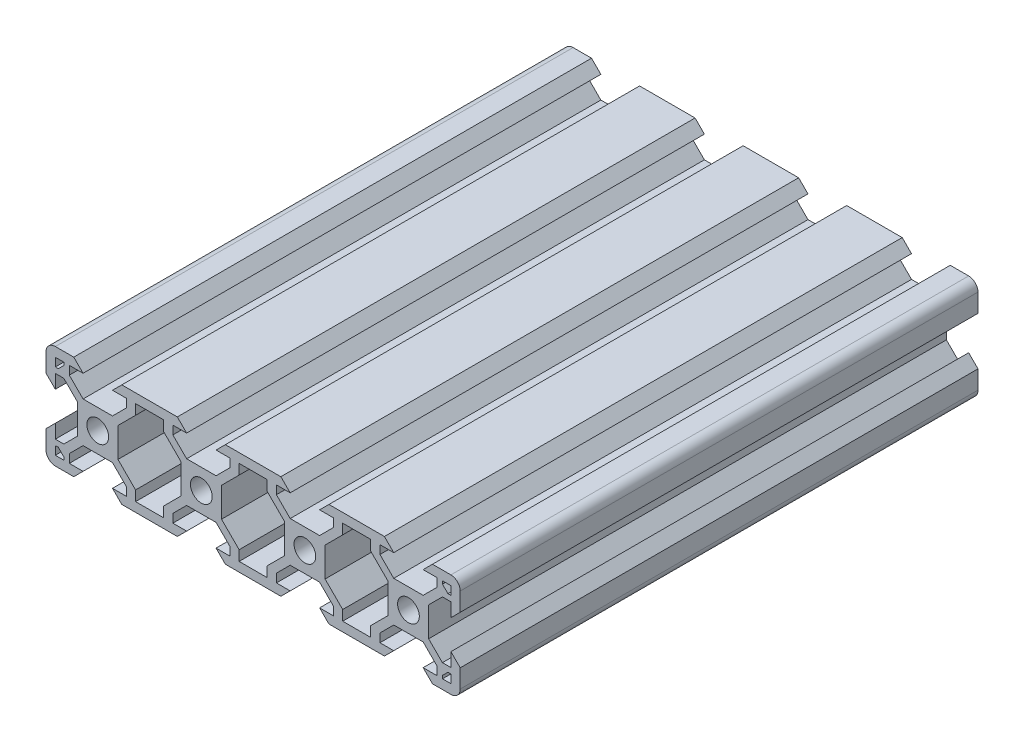
SolidWorks part; units mm, degrees
material "5052-H38, Barre (SS)"
ref_plane "Plan de face" through (0, 0, 0) normal (0, 0, 1) x (1, 0, 0)
ref_plane "Plan de dessus" through (0, 0, 0) normal (0, 1, 0) x (1, 0, 0)
ref_plane "Plan de droite" through (0, 0, 0) normal (1, 0, 0) x (0, 0, -1)
sketch "Esquisse1" plane through (0, 0, 0) normal (0, 0, 1) x (1, 0, 0)
  line L0 (0, 0) -> (0, 10) construction
  line L1 (0, 0) -> (-40, 0) construction
  line L2 (-40, 10) -> (-30, 0) construction
  line L3 (-30, 0) -> (-20, 10) construction
  line L4 (-20, 10) -> (-10, 0) construction
  line L5 (-10, 0) -> (0, 10) construction
  line L6 (-10, 0) -> (-10, 10) construction
  line L7 (-20, 10) -> (-20, 0) construction
  line L8 (-40, 0) -> (-40, 10) construction
  line L9 (-38.2, 10) -> (-34.64, 10)
  line L10 (-34.64, 10) -> (-32.84, 8.2)
  line L11 (-32.84, 8.2) -> (-35.4993, 8.2)
  line L12 (-35.4993, 8.2) -> (-35.4993, 6.56)
  line L13 (-35.4993, 6.56) -> (-32.84, 3.9007)
  line L14 (-32.84, 3.9007) -> (-27.16, 3.9007)
  line L15 (-30, 0) -> (-30, 10) construction
  line L16 (-33.9007, 2.84) -> (-33.9007, 0)
  line L17 (-36.56, 5.4993) -> (-33.9007, 2.84)
  line L18 (-38.2, 5.4993) -> (-36.56, 5.4993)
  line L19 (-38.2, 2.84) -> (-38.2, 5.4993)
  line L20 (-40, 4.64) -> (-38.2, 2.84)
  line L21 (-40, 8.2) -> (-40, 4.64)
  line L22 (-38.2, 8.2) -> (-38.2, 6.5693)
  line L23 (-38.2, 6.5693) -> (-37.63, 6.5693)
  line L24 (-37.63, 6.5693) -> (-36.5693, 7.63)
  line L25 (-36.5693, 7.63) -> (-36.5693, 8.2)
  line L26 (-36.5693, 8.2) -> (-38.2, 8.2)
  line L27 (-17.3, 6.2393) -> (-17.3, 8.2)
  line L28 (-13.9007, 2.84) -> (-17.3, 6.2393)
  line L29 (-13.9007, -2.84) -> (-13.9007, 2.84)
  line L30 (-14.64, 10) -> (-12.84, 8.2)
  line L31 (-12.84, 8.2) -> (-15.4993, 8.2)
  line L32 (-15.4993, 8.2) -> (-15.4993, 6.56)
  line L33 (-15.4993, 6.56) -> (-12.84, 3.9007)
  line L34 (-12.84, 3.9007) -> (-7.16, 3.9007)
  line L35 (-5.36, 10) -> (-7.16, 8.2)
  line L36 (-7.16, 8.2) -> (-4.5007, 8.2)
  line L37 (-4.5007, 8.2) -> (-4.5007, 6.56)
  line L38 (-4.5007, 6.56) -> (-7.16, 3.9007)
  line L39 (-5.36, 10) -> (5.36, 10)
  line L40 (-6.0993, -2.84) -> (-6.0993, 2.84)
  line L41 (-6.0993, 2.84) -> (-2.7, 6.2393)
  line L42 (-2.7, 6.2393) -> (-2.7, 8.2)
  line L43 (-2.7, 8.2) -> (2.7, 8.2)
  line L44 (-25.36, 10) -> (-27.16, 8.2)
  line L45 (-7.16, 3.9007) -> (-6.0993, 2.84) construction
  line L46 (-36.5693, -7.63) -> (-36.5693, -8.2)
  line L47 (-37.63, -6.5693) -> (-36.5693, -7.63)
  line L48 (-38.2, -6.5693) -> (-37.63, -6.5693)
  line L49 (-38.2, -8.2) -> (-38.2, -6.5693)
  line L50 (-27.16, 8.2) -> (-24.5007, 8.2)
  line L51 (-24.5007, 8.2) -> (-24.5007, 6.56)
  line L52 (-24.5007, 6.56) -> (-27.16, 3.9007)
  line L53 (-25.36, 10) -> (-14.64, 10)
  line L54 (-26.0993, -2.84) -> (-26.0993, 2.84)
  line L55 (-26.0993, 2.84) -> (-22.7, 6.2393)
  line L56 (-22.7, 6.2393) -> (-22.7, 8.2)
  line L57 (-22.7, 8.2) -> (-17.3, 8.2)
  line L58 (-27.16, 3.9007) -> (-26.0993, 2.84) construction
  line L59 (-26.0993, 2.84) -> (-26.0962, 2.8177) construction
  line L60 (-36.5693, -8.2) -> (-38.2, -8.2)
  line L61 (-26.0993, -2.84) -> (-22.7, -6.2393)
  line L62 (-22.7, -6.2393) -> (-22.7, -8.2)
  line L63 (-22.7, -8.2) -> (-17.3, -8.2)
  line L64 (-17.3, -6.2393) -> (-17.3, -8.2)
  line L65 (-13.9007, -2.84) -> (-17.3, -6.2393)
  line L66 (-2.7, -8.2) -> (2.7, -8.2)
  line L67 (-2.7, -6.2393) -> (-2.7, -8.2)
  line L68 (-6.0993, -2.84) -> (-2.7, -6.2393)
  line L69 (-5.36, -10) -> (5.36, -10)
  line L70 (-5.36, -10) -> (-7.16, -8.2)
  line L71 (-7.16, -8.2) -> (-4.5007, -8.2)
  line L72 (-4.5007, -8.2) -> (-4.5007, -6.56)
  line L73 (-4.5007, -6.56) -> (-7.16, -3.9007)
  line L74 (-12.84, -3.9007) -> (-7.16, -3.9007)
  line L75 (-15.4993, -6.56) -> (-12.84, -3.9007)
  line L76 (-15.4993, -8.2) -> (-15.4993, -6.56)
  line L77 (-12.84, -8.2) -> (-15.4993, -8.2)
  line L78 (-14.64, -10) -> (-12.84, -8.2)
  line L79 (-25.36, -10) -> (-14.64, -10)
  line L80 (-25.36, -10) -> (-27.16, -8.2)
  line L81 (-27.16, -8.2) -> (-24.5007, -8.2)
  line L82 (-24.5007, -8.2) -> (-24.5007, -6.56)
  line L83 (-24.5007, -6.56) -> (-27.16, -3.9007)
  line L84 (-32.84, -3.9007) -> (-27.16, -3.9007)
  line L85 (-35.4993, -6.56) -> (-32.84, -3.9007)
  line L86 (-35.4993, -8.2) -> (-35.4993, -6.56)
  line L87 (-32.84, -8.2) -> (-35.4993, -8.2)
  line L88 (-34.64, -10) -> (-32.84, -8.2)
  line L89 (-38.2, -10) -> (-34.64, -10)
  line L90 (-40, -8.2) -> (-40, -4.64)
  line L91 (-40, -4.64) -> (-38.2, -2.84)
  line L92 (-38.2, -2.84) -> (-38.2, -5.4993)
  line L93 (-38.2, -5.4993) -> (-36.56, -5.4993)
  line L94 (-36.56, -5.4993) -> (-33.9007, -2.84)
  line L95 (-33.9007, -2.84) -> (-33.9007, 0)
  line L96 (36.5693, 8.2) -> (38.2, 8.2)
  line L97 (36.5693, 7.63) -> (36.5693, 8.2)
  line L98 (37.63, 6.5693) -> (36.5693, 7.63)
  line L99 (38.2, 6.5693) -> (37.63, 6.5693)
  line L100 (38.2, 8.2) -> (38.2, 6.5693)
  line L101 (36.5693, -8.2) -> (38.2, -8.2)
  line L102 (36.5693, -7.63) -> (36.5693, -8.2)
  line L103 (37.63, -6.5693) -> (36.5693, -7.63)
  line L104 (38.2, -6.5693) -> (37.63, -6.5693)
  line L105 (38.2, -8.2) -> (38.2, -6.5693)
  line L106 (13.9007, -2.84) -> (17.3, -6.2393)
  line L107 (17.3, -6.2393) -> (17.3, -8.2)
  line L108 (22.7, -8.2) -> (17.3, -8.2)
  line L109 (22.7, -6.2393) -> (22.7, -8.2)
  line L110 (26.0993, -2.84) -> (22.7, -6.2393)
  line L111 (26.0993, -2.84) -> (26.0993, 2.84)
  line L112 (26.0993, 2.84) -> (22.7, 6.2393)
  line L113 (22.7, 6.2393) -> (22.7, 8.2)
  line L114 (22.7, 8.2) -> (17.3, 8.2)
  line L115 (17.3, 6.2393) -> (17.3, 8.2)
  line L116 (13.9007, 2.84) -> (17.3, 6.2393)
  line L117 (13.9007, -2.84) -> (13.9007, 2.84)
  line L118 (2.7, -6.2393) -> (2.7, -8.2)
  line L119 (6.0993, -2.84) -> (2.7, -6.2393)
  line L120 (6.0993, -2.84) -> (6.0993, 2.84)
  line L121 (6.0993, 2.84) -> (2.7, 6.2393)
  line L122 (2.7, 6.2393) -> (2.7, 8.2)
  line L123 (5.36, -10) -> (7.16, -8.2)
  line L124 (7.16, -8.2) -> (4.5007, -8.2)
  line L125 (4.5007, -8.2) -> (4.5007, -6.56)
  line L126 (4.5007, -6.56) -> (7.16, -3.9007)
  line L127 (12.84, -3.9007) -> (7.16, -3.9007)
  line L128 (15.4993, -6.56) -> (12.84, -3.9007)
  line L129 (15.4993, -8.2) -> (15.4993, -6.56)
  line L130 (12.84, -8.2) -> (15.4993, -8.2)
  line L131 (14.64, -10) -> (12.84, -8.2)
  line L132 (25.36, -10) -> (14.64, -10)
  line L133 (25.36, -10) -> (27.16, -8.2)
  line L134 (27.16, -8.2) -> (24.5007, -8.2)
  line L135 (24.5007, -8.2) -> (24.5007, -6.56)
  line L136 (24.5007, -6.56) -> (27.16, -3.9007)
  line L137 (32.84, -3.9007) -> (27.16, -3.9007)
  line L138 (35.4993, -6.56) -> (32.84, -3.9007)
  line L139 (35.4993, -8.2) -> (35.4993, -6.56)
  line L140 (32.84, -8.2) -> (35.4993, -8.2)
  line L141 (34.64, -10) -> (32.84, -8.2)
  line L142 (38.2, -10) -> (34.64, -10)
  line L143 (40, -8.2) -> (40, -4.64)
  line L144 (40, -4.64) -> (38.2, -2.84)
  line L145 (38.2, -2.84) -> (38.2, -5.4993)
  line L146 (38.2, -5.4993) -> (36.56, -5.4993)
  line L147 (36.56, -5.4993) -> (33.9007, -2.84)
  line L148 (33.9007, -2.84) -> (33.9007, 0)
  line L149 (33.9007, 2.84) -> (33.9007, 0)
  line L150 (36.56, 5.4993) -> (33.9007, 2.84)
  line L151 (38.2, 5.4993) -> (36.56, 5.4993)
  line L152 (38.2, 2.84) -> (38.2, 5.4993)
  line L153 (40, 4.64) -> (38.2, 2.84)
  line L154 (40, 8.2) -> (40, 4.64)
  line L155 (38.2, 10) -> (34.64, 10)
  line L156 (34.64, 10) -> (32.84, 8.2)
  line L157 (32.84, 8.2) -> (35.4993, 8.2)
  line L158 (35.4993, 8.2) -> (35.4993, 6.56)
  line L159 (35.4993, 6.56) -> (32.84, 3.9007)
  line L160 (32.84, 3.9007) -> (27.16, 3.9007)
  line L161 (24.5007, 6.56) -> (27.16, 3.9007)
  line L162 (24.5007, 8.2) -> (24.5007, 6.56)
  line L163 (27.16, 8.2) -> (24.5007, 8.2)
  line L164 (25.36, 10) -> (27.16, 8.2)
  line L165 (25.36, 10) -> (14.64, 10)
  line L166 (14.64, 10) -> (12.84, 8.2)
  line L167 (12.84, 8.2) -> (15.4993, 8.2)
  line L168 (15.4993, 8.2) -> (15.4993, 6.56)
  line L169 (15.4993, 6.56) -> (12.84, 3.9007)
  line L170 (12.84, 3.9007) -> (7.16, 3.9007)
  line L171 (4.5007, 6.56) -> (7.16, 3.9007)
  line L172 (4.5007, 8.2) -> (4.5007, 6.56)
  line L173 (7.16, 8.2) -> (4.5007, 8.2)
  line L174 (5.36, 10) -> (7.16, 8.2)
  circle A0 centre (-30, 0) radius 2.1
  circle A1 centre (-10, 0) radius 2.1
  arc A2 (-38.2, 10) -> (-40, 8.2) centre (-38.2, 8.2) ccw
  arc A3 (-38.2, -10) -> (-40, -8.2) centre (-38.2, -8.2) cw
  circle A4 centre (30, 0) radius 2.1
  circle A5 centre (10, 0) radius 2.1
  arc A6 (38.2, -10) -> (40, -8.2) centre (38.2, -8.2) ccw
  arc A7 (38.2, 10) -> (40, 8.2) centre (38.2, 8.2) cw
  point P21 (-37.0997, 7.0997)
  point P36 (-20, 8.2)
  point P47 (-10, 3.9007)
  point P54 (-6.6297, 3.3703)
  point P61 (-30, 3.9007)
  point P71 (-26.0993, 0)
  point P76 (-13.9007, 0)
  point P80 (-6.0993, 0)
  point P135 (0, -8.2)
  point P140 (0, 8.2)
  point P141 (0, -10)
  dimension "D3" = 4.2
  dimension "D4" = 4.2
  dimension "D1" = 40
  dimension "D2" = 10
  dimension "D5" = 5.68
  dimension "D6" = 1.5
  dimension "D7" = 1.64
  dimension "D8" = 1.8
  dimension "D9" = 1.07
  dimension "D11" = 5.4
extrude "Boss.-Extru.1" add sketch "Esquisse1" along normal mid plane 100
